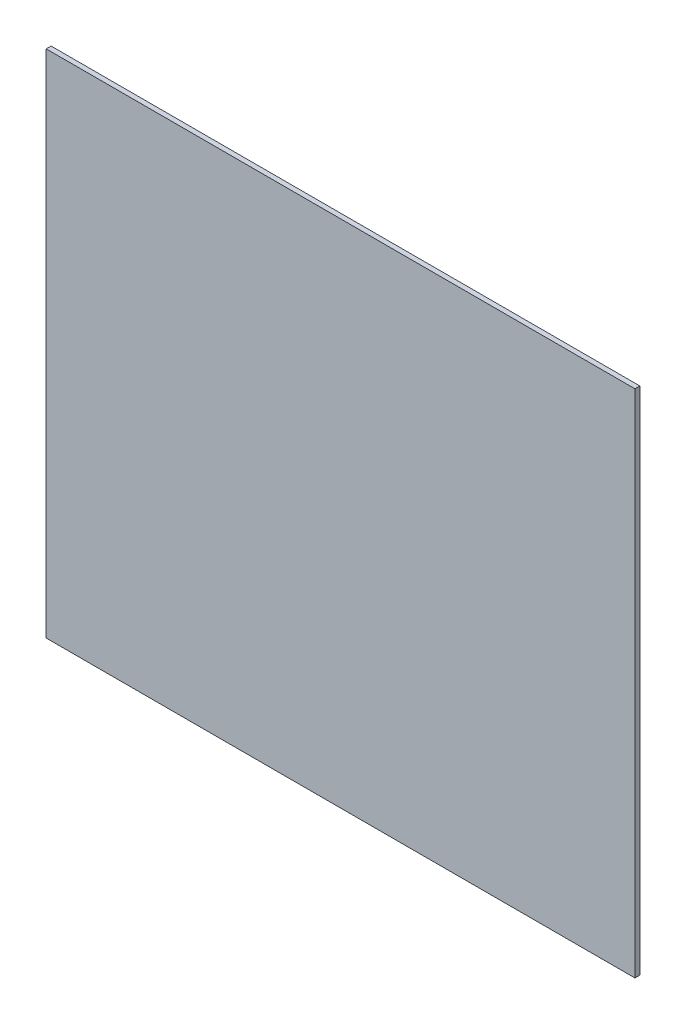
SolidWorks part; units mm, degrees
ref_plane "Front Plane" through (0, 0, 0) normal (0, 0, 1) x (1, 0, 0)
ref_plane "Top Plane" through (0, 0, 0) normal (0, 1, 0) x (1, 0, 0)
ref_plane "Right Plane" through (0, 0, 0) normal (1, 0, 0) x (0, 0, -1)
sketch "Sketch1" plane through (0, 0, 0) normal (0, 0, 1) x (1, 0, 0)
  line L1 (-95.25, 82.55) -> (95.25, 82.55)
  line L2 (-95.25, 82.55) -> (-95.25, -82.55)
  line L3 (-95.25, -82.55) -> (95.25, -82.55)
  line L4 (95.25, 82.55) -> (95.25, -82.55)
  line L5 (-95.25, 82.55) -> (95.25, -82.55) construction
  line L6 (-95.25, -82.55) -> (95.25, 82.55) construction
  point P0 (0, 0)
  dimension "D1" = 190.5
  dimension "D2" = 165.1
extrude "Boss-Extrude1" add sketch "Sketch1" along normal blind 1.5875
